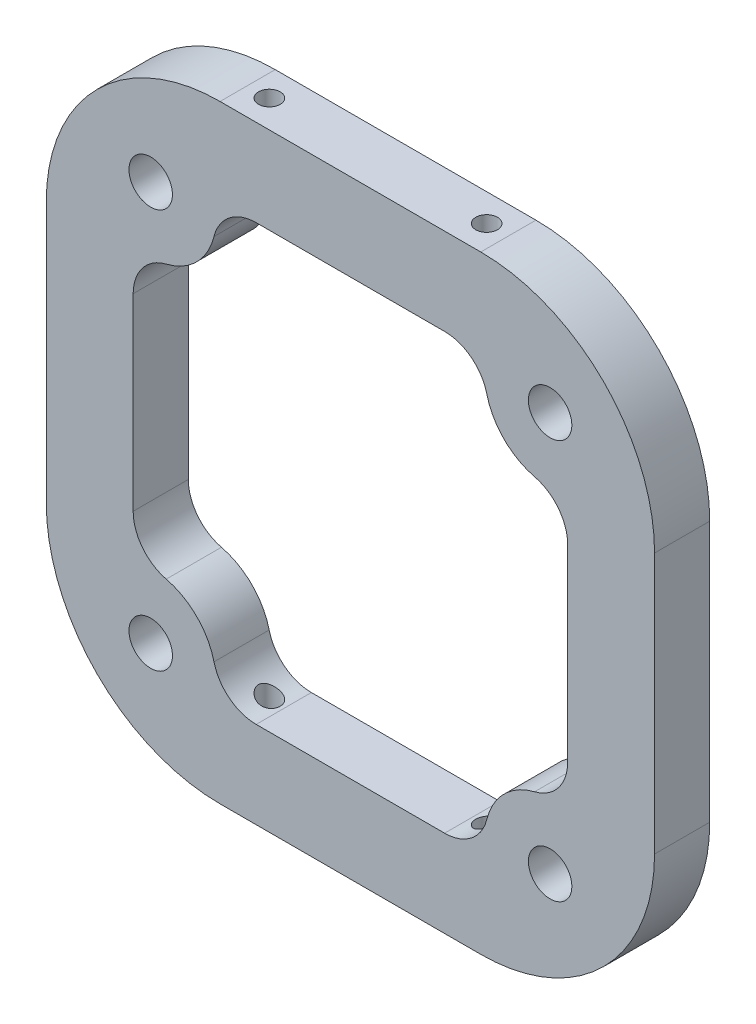
SolidWorks part; units mm, degrees
material "6061 Alloy"
ref_plane "Front Plane" through (0, 0, 0) normal (0, 0, 1) x (1, 0, 0)
ref_plane "Top Plane" through (0, 0, 0) normal (0, 1, 0) x (1, 0, 0)
ref_plane "Right Plane" through (0, 0, 0) normal (1, 0, 0) x (0, 0, -1)
sketch "Sketch1" plane through (0, 0, 0) normal (0, 0, 1) x (1, 0, 0)
  line L0 (-15.7578, 25) -> (15.7578, 25)
  line L1 (-22.981, -22.981) -> (22.981, -22.981) construction
  line L2 (-22.981, -22.981) -> (-22.981, 22.981) construction
  line L3 (-22.981, 22.981) -> (22.981, 22.981) construction
  line L4 (22.981, -22.981) -> (22.981, 22.981) construction
  line L5 (-22.981, -22.981) -> (22.981, 22.981) construction
  line L6 (-22.981, 22.981) -> (22.981, -22.981) construction
  line L7 (25, 15.7578) -> (25, -15.7578)
  line L8 (15.7578, -25) -> (-15.7578, -25)
  line L9 (-25, -15.7578) -> (-25, 15.7578)
  line L11 (-35, -35) -> (35, -35)
  line L12 (-35, -35) -> (-35, 35)
  line L13 (-35, 35) -> (35, 35)
  line L14 (35, -35) -> (35, 35)
  line L15 (-35, -35) -> (35, 35) construction
  line L16 (-35, 35) -> (35, -35) construction
  circle A0 centre (0, 0) radius 25 construction
  circle A1 centre (0, 0) radius 32.5 construction
  arc A2 (-15.7578, 25) -> (-25, 15.7578) centre (-22.981, 22.981) ccw construction
  arc A3 (-25, -15.7578) -> (-15.7578, -25) centre (-22.981, -22.981) ccw construction
  arc A4 (15.7578, -25) -> (25, -15.7578) centre (22.981, -22.981) ccw construction
  arc A5 (25, 15.7578) -> (15.7578, 25) centre (22.981, 22.981) ccw construction
  arc A6 (15.7578, 25) -> (25, 15.7578) centre (22.981, 22.981) ccw
  arc A7 (-25, 15.7578) -> (-15.7578, 25) centre (-22.981, 22.981) ccw
  arc A8 (-15.7578, -25) -> (-25, -15.7578) centre (-22.981, -22.981) ccw
  arc A9 (25, -15.7578) -> (15.7578, -25) centre (22.981, -22.981) ccw
  dimension "D1" = 50
  dimension "D2" = 65
  dimension "D3" = 15
  dimension "D4" = 10
extrude ".125 in sheet" add sketch "Sketch1" along normal mid plane 6.35 contours A5 A0 A2 A3 A4 | A0 A2 | A0 A5 | A0 A4 | A0 A3 | A0 A3 | A0 A2 | A0 A5 | A0 A4 | L11 L14 L13 L12 L7 A9 L8 A8 L9 A7 L0 A6
fillet "Fillet1" radius 5 8 edges at (25, -15.7578, 0) (15.7578, -25, 0) (-15.7578, -25, 0) (-25, -15.7578, 0) (25, 15.7578, 0) (15.7578, 25, 0) (-25, 15.7578, 0) (-15.7578, 25, 0)
fillet "Fillet2" radius 20 4 edges at (-35, -35, 0) (35, -35, 0) (35, 35, 0) (-35, 35, 0)
hole_wizard "Ø5.0 Reamed over for shoulder bolt" positions "Sketch6" profile "Sketch5" hole size "Ø5.0" standard "ANSI Metric" end condition through all
sketch "Sketch6" plane through (-38.6077, 4.3708, 3.175) normal (0, 0, 1) x (1, 0, 0)
  point P0 (15.6267, 18.6101)
  point P3 (61.5886, 18.6101)
  point P6 (61.5886, -27.3518)
  point P9 (15.6267, -27.3518)
sketch "Sketch5" plane through (-22.981, 22.981, 3.175) normal (1, 0, 0) x (0, -1, 0)
  line L0 (0, 0) -> (0, 6.35)
  line L1 (0, 6.35) -> (2.5, 6.35)
  line L2 (2.5, 6.35) -> (2.5, 0)
  line L5 (2.5, 0) -> (0, 0)
  line L11 (0, -6.35) -> (0, 107.95) construction
  dimension "Thru Hole Dia." = 5
  dimension "Thru Hole Depth" = 6.35
hole_wizard "M3x0.5 Tapped Hole1" positions "Sketch12" profile "Sketch13" tap size "M3x0.5" standard "ANSI Metric"
sketch "Sketch12" plane through (0, 35, 0) normal (0, 1, 0) x (1, 0, 0)
  line L0 (-12.5, 0) -> (12.5, 0) construction
  line L2 (-15, 3.175) -> (15, 3.175) construction
  point P8 (-12.5, 0)
  point P10 (12.5, 0)
  dimension "D1" = 25
sketch "Sketch13" plane through (-12.5, 35, 0) normal (1, 0, 0) x (0, 0, 1)
  line L0 (0, 0) -> (0, 70)
  line L1 (0, 70) -> (1.25, 70)
  line L2 (1.25, 70) -> (1.25, 0)
  line L5 (1.25, 0) -> (0, 0)
  line L11 (0, -6.35) -> (0, 107.95) construction
  dimension "Thru Tap Drill Dia." = 2.5
  dimension "Thru Tap Drill Depth" = 70
cosmetic thread "Hole Thread1" parameters "D2"=3
cosmetic thread "Hole Thread2" parameters "D2"=3
mirror "Mirror1" about plane through (0, 0, 0) normal (0, 1, 0) of "M3x0.5 Tapped Hole1"
